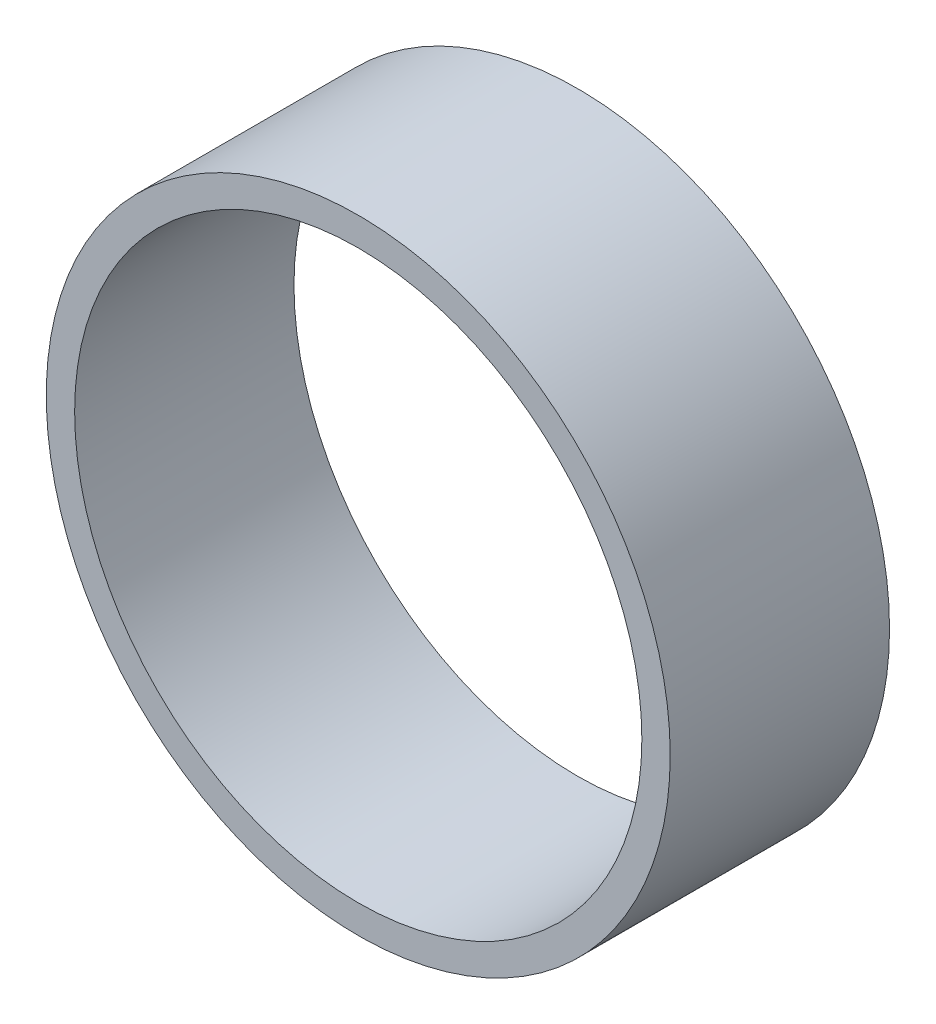
SolidWorks part; units mm, degrees
ref_plane "Front Plane" through (0, 0, 0) normal (0, 0, 1) x (1, 0, 0)
ref_plane "Top Plane" through (0, 0, 0) normal (0, 1, 0) x (1, 0, 0)
ref_plane "Right Plane" through (0, 0, 0) normal (1, 0, 0) x (0, 0, -1)
sketch "Sketch1" plane through (0, 0, 0) normal (0, 0, 1) x (1, 0, 0)
  circle A0 centre (-43.2127, 1.4419) radius 8.25
  dimension "D1" = 16.5
extrude "Boss-Extrude1" add sketch "Sketch1" along normal blind 5.8
sketch "Sketch2" plane through (0, 0, 5.8) normal (0, 0, 1) x (1, 0, 0)
  circle A0 centre (-43.2127, 1.4419) radius 7.5
  dimension "D1" = 15
extrude "Cut-Extrude1" cut sketch "Sketch2" against normal blind 5.8
